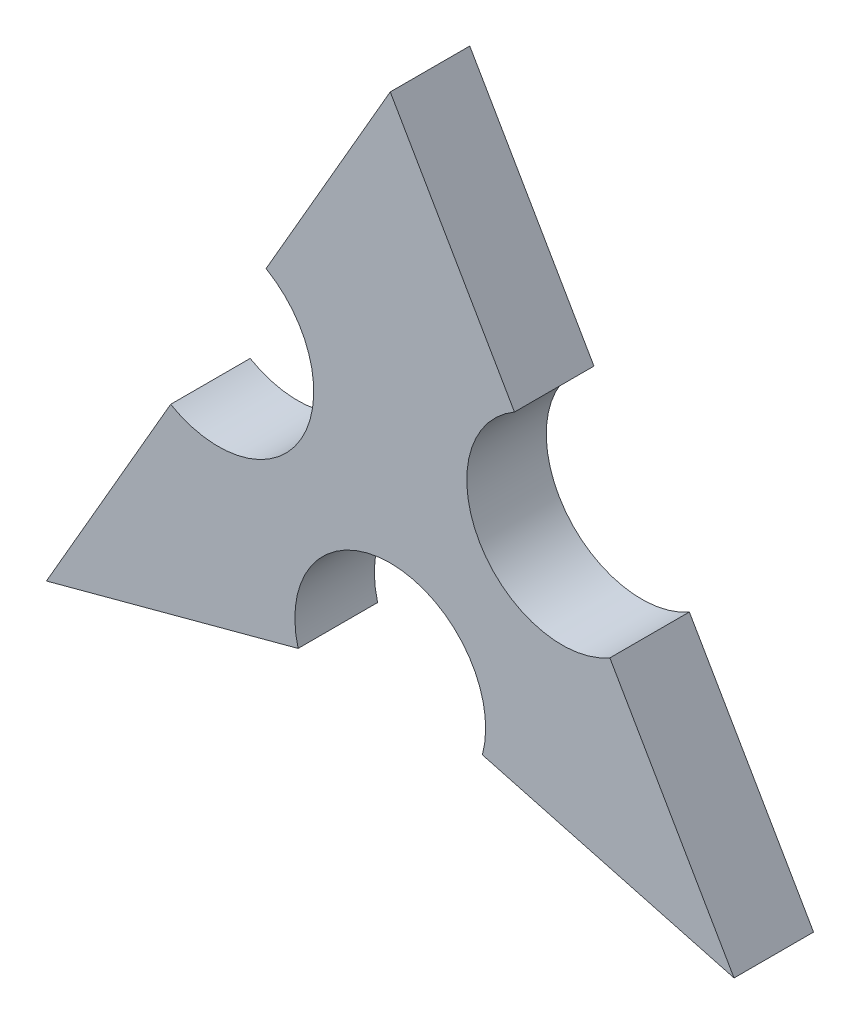
SolidWorks part; units mm, degrees
material "Cast Stainless Steel"
ref_plane "Front Plane" through (0, 0, 0) normal (0, 0, 1) x (1, 0, 0)
ref_plane "Top Plane" through (0, 0, 0) normal (0, 1, 0) x (1, 0, 0)
ref_plane "Right Plane" through (0, 0, 0) normal (1, 0, 0) x (0, 0, -1)
sketch "Sketch1" plane through (0, 0, 0) normal (0, 0, 1) x (1, 0, 0)
  line L0 (0, 149.8224) -> (31.25, 95.6958)
  line L1 (86.5, 0) -> (23.1822, 16.9659)
  line L2 (-23.1822, 16.9659) -> (-86.5, 0)
  line L3 (-86.5, 0) -> (-55.25, 54.1266)
  line L4 (55.25, 54.1266) -> (86.5, 0)
  line L5 (-31.25, 95.6958) -> (0, 149.8224)
  arc A1 (31.25, 95.6958) -> (55.25, 54.1266) centre (43.25, 74.9112) ccw
  arc A2 (-55.25, 54.1266) -> (-31.25, 95.6958) centre (-43.25, 74.9112) ccw
  arc A3 (23.1822, 16.9659) -> (-23.1822, 16.9659) centre (0, 23.1776) ccw
  point P9 (0, 0)
  point P14 (0, 0)
  point P15 (44.2319, 73.2105)
  point P16 (-40.3281, 73.2986)
  point P17 (0, 0)
  point P18 (0, 0)
  dimension "D5" = 48
  dimension "D6" = 48
  dimension "D7" = 48
  dimension "D1" = 173
  dimension "D2" = 173
  dimension "D3" = 173
  dimension "D4" = 45
  dimension "D8" = 86.5
  dimension "D9" = 45
extrude "Boss-Extrude1" add sketch "Sketch1" along normal mid plane 20
